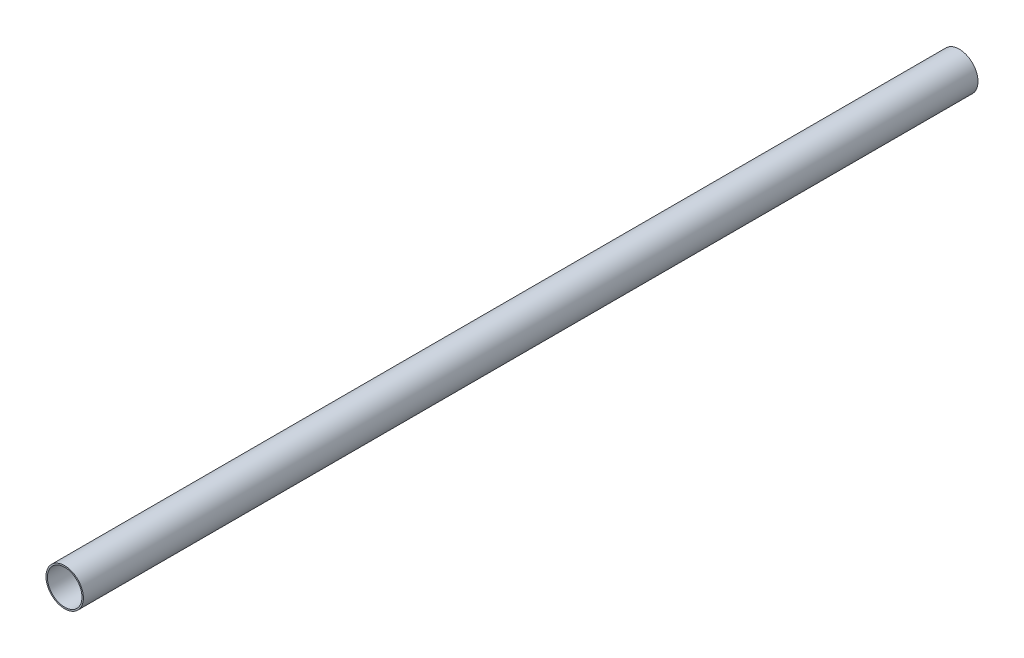
SolidWorks part; units mm, degrees
ref_plane "Front Plane" through (0, 0, 0) normal (0, 0, 1) x (1, 0, 0)
ref_plane "Top Plane" through (0, 0, 0) normal (0, 1, 0) x (1, 0, 0)
ref_plane "Right Plane" through (0, 0, 0) normal (1, 0, 0) x (0, 0, -1)
sketch "Sketch1" plane through (0, 0, 0) normal (0, 0, 1) x (1, 0, 0)
  circle A0 centre (0, 0) radius 16
  circle A1 centre (0, 0) radius 14.8
  dimension "D1" = 32
  dimension "D2" = 1.2
extrude "Boss-Extrude1" add sketch "Sketch1" along normal blind 765
